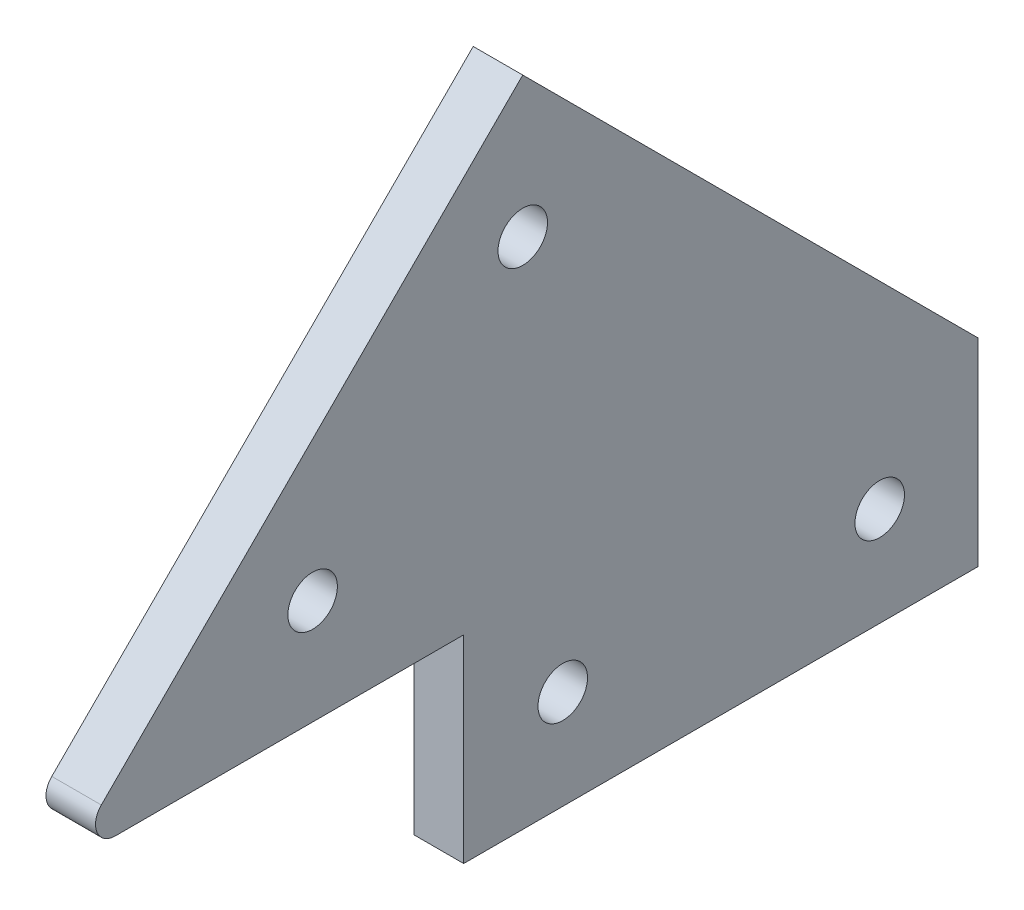
SolidWorks part; units mm, degrees
ref_plane "前视基准面" through (0, 0, 0) normal (0, 0, 1) x (1, 0, 0)
ref_plane "上视基准面" through (0, 0, 0) normal (0, 1, 0) x (1, 0, 0)
ref_plane "右视基准面" through (0, 0, 0) normal (1, 0, 0) x (0, 0, -1)
sketch "草图1" plane through (0, 0, 0) normal (1, 0, 0) x (0, 0, -1)
  line L0 (-159.0381, 45.9619) -> (-113.0761, 0)
  line L2 (-205, 0) -> (-159.0381, 45.9619)
  line L20 (-165, 0) -> (-165, -20)
  line L21 (-165, -20) -> (-113.0761, -20)
  line L22 (-113.0761, -20) -> (-113.0761, 0)
  line L26 (-165, -10) -> (-113.0761, -10) construction
  line L27 (-165, 0) -> (-205, 0)
  circle A44 centre (-155, -10) radius 2.5
  circle A45 centre (-123, -10) radius 2.5
  circle A48 centre (-180.2513, 10.6066) radius 2.5
  circle A56 centre (-159.0381, 31.8198) radius 2.5
  point P10 (0, 0)
  dimension "D17" = 5
  dimension "D18" = 5
  dimension "D22" = 5
  dimension "D3" = 2
  dimension "D4" = 45
  dimension "D5" = 10
  dimension "D10" = 65
  dimension "D15" = 40
  dimension "D19" = 32
  dimension "D20" = 10
  dimension "D21" = 20
  dimension "D23" = 10
extrude "凸台-拉伸1" add sketch "草图1" along normal blind 5
fillet "圆角1" radius 2 1 edges at (2.5, 0, 205)
